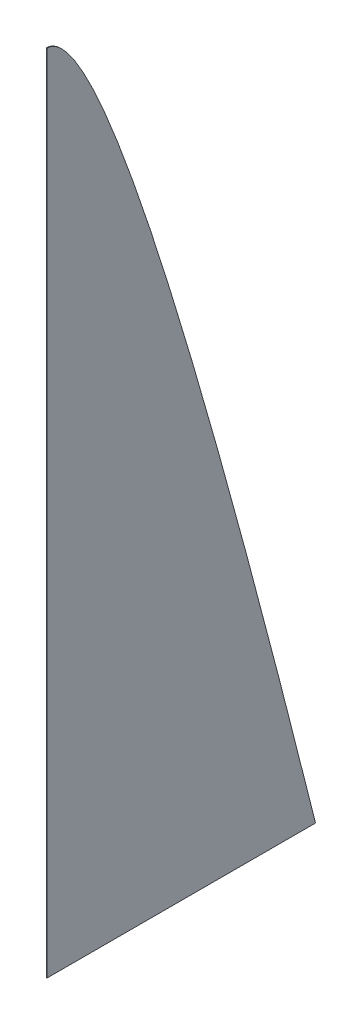
SolidWorks part; units mm, degrees
ref_plane "Front Plane" through (0, 0, 0) normal (0, 0, 1) x (1, 0, 0)
ref_plane "Top Plane" through (0, 0, 0) normal (0, 1, 0) x (1, 0, 0)
ref_plane "Right Plane" through (0, 0, 0) normal (1, 0, 0) x (0, 0, -1)
sketch "Sketch1" plane through (0, 0, 0) normal (1, 0, 0) x (0, 0, -1)
  line L0 (0, 0) -> (0, 1200)
  line L2 (400, 0) -> (0, 0)
  line L3 (0, 1200) -> (100, 1200) construction
  line L4 (100, 1200) -> (400, 0) construction
  line L5 (0, 1200) -> (400, 0) construction
  spline S0 degree 2 poles (0, 1200) (100, 1200) (400, 0) knots 0 0 0 1 1 1
  dimension "D1" = 1200
  dimension "D2" = 400
  dimension "D3" = 100
extrude "Boss-Extrude1" add sketch "Sketch1" along normal blind 1
